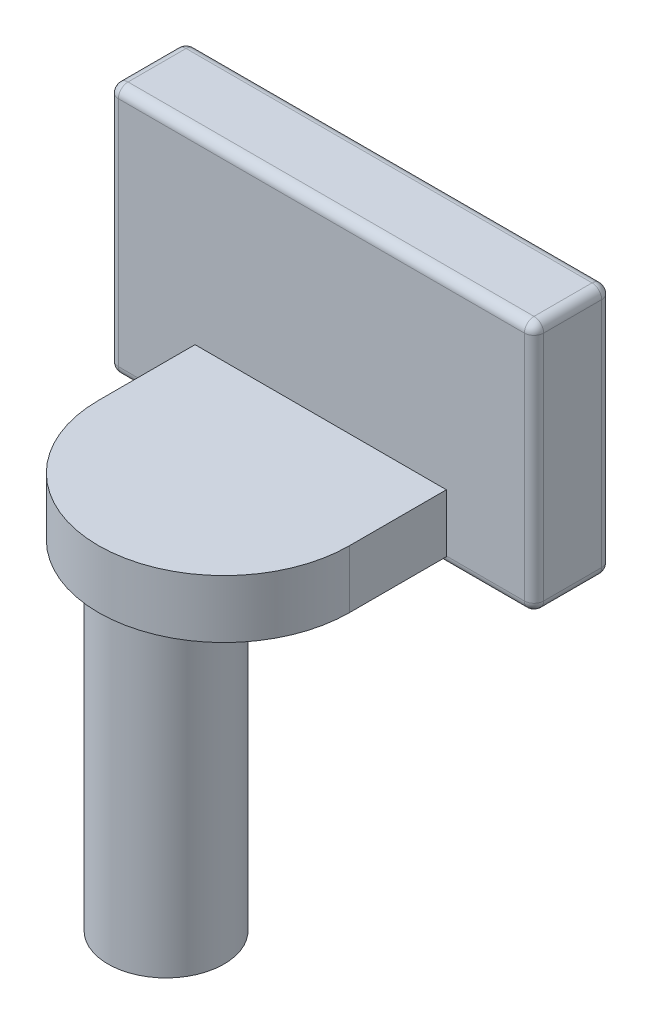
SolidWorks part; units mm, degrees
ref_plane "Front Plane" through (0, 0, 0) normal (0, 0, 1) x (1, 0, 0)
ref_plane "Top Plane" through (0, 0, 0) normal (0, 1, 0) x (1, 0, 0)
ref_plane "Right Plane" through (0, 0, 0) normal (1, 0, 0) x (0, 0, -1)
sketch "Sketch1" plane through (0, 0, 0) normal (0, 0, 1) x (1, 0, 0)
  line L1 (-110, 65) -> (110, 65)
  line L2 (-110, 65) -> (-110, -65)
  line L3 (-110, -65) -> (110, -65)
  line L4 (110, 65) -> (110, -65)
  line L5 (0, -65) -> (0, 65) construction
  line L6 (-110, 0) -> (110, 0) construction
  point P0 (0, 0)
  dimension "D1" = 220
  dimension "D2" = 130
extrude "Boss-Extrude1" add sketch "Sketch1" along normal blind 40 contours L1 L4 L3 L2
fillet "Fillet1" radius 5 12 edges at (-110, -65, 20) (0, -65, 0) (-110, 0, 0) (-110, 65, 20) (0, 65, 0) (0, 65, 40) (0, -65, 40) (-110, 0, 40) (110, -65, 20) (110, 0, 40) (110, 65, 20) (110, 0, 0)
sketch "Sketch2" plane through (0, 0, 0) normal (0, 0, -1) x (-1, 0, 0)
  line L1 (-97.5, 52.5) -> (97.5, 52.5)
  line L2 (-97.5, 52.5) -> (-97.5, -52.5)
  line L3 (-97.5, -52.5) -> (97.5, -52.5)
  line L4 (97.5, 52.5) -> (97.5, -52.5)
  line L5 (0, -52.5) -> (0, 52.5) construction
  line L6 (-97.5, 0) -> (97.5, 0) construction
  point P0 (0, 0)
  dimension "D1" = 195
  dimension "D2" = 105
extrude "Cut-Extrude1" cut sketch "Sketch2" against normal blind 15
fillet "Fillet2" radius 3 4 edges at (-97.5, 0, 0) (0, -52.5, 0) (97.5, 0, 0) (0, 52.5, 0)
ref_plane "Plane4" through (0, -60, 0) normal (0, 1, 0) x (1, 0, 0)
sketch "Sketch4" plane through (0, -60, 0) normal (0, 1, 0) x (1, 0, 0)
  line L0 (0, 78.3357) -> (0, -130.1927) construction
  line L2 (-65, -40.3432) -> (65, -40.3432)
  line L3 (-65, -40.3432) -> (-65, -90.3432)
  line L5 (65, -40.3432) -> (65, -90.3432)
  line L6 (0, -90.3432) -> (0, -40.3432) construction
  arc A0 (-65, -90.3432) -> (65, -90.3432) centre (0, -90.3432) ccw
  point P2 (0, -76.7817)
  dimension "D1" = 130
  dimension "D2" = 50
extrude "Boss-Extrude3" add sketch "Sketch4" along normal blind 30 separate body
sketch "Sketch7" plane through (0, -60, 0) normal (0, -1, 0) x (1, 0, 0)
  line L0 (65, 40.3432) -> (-65, 40.3432) construction
  circle A0 centre (0, 120.3432) radius 30
  dimension "D1" = 80
extrude "Boss-Extrude5" add sketch "Sketch7" along normal blind 160
